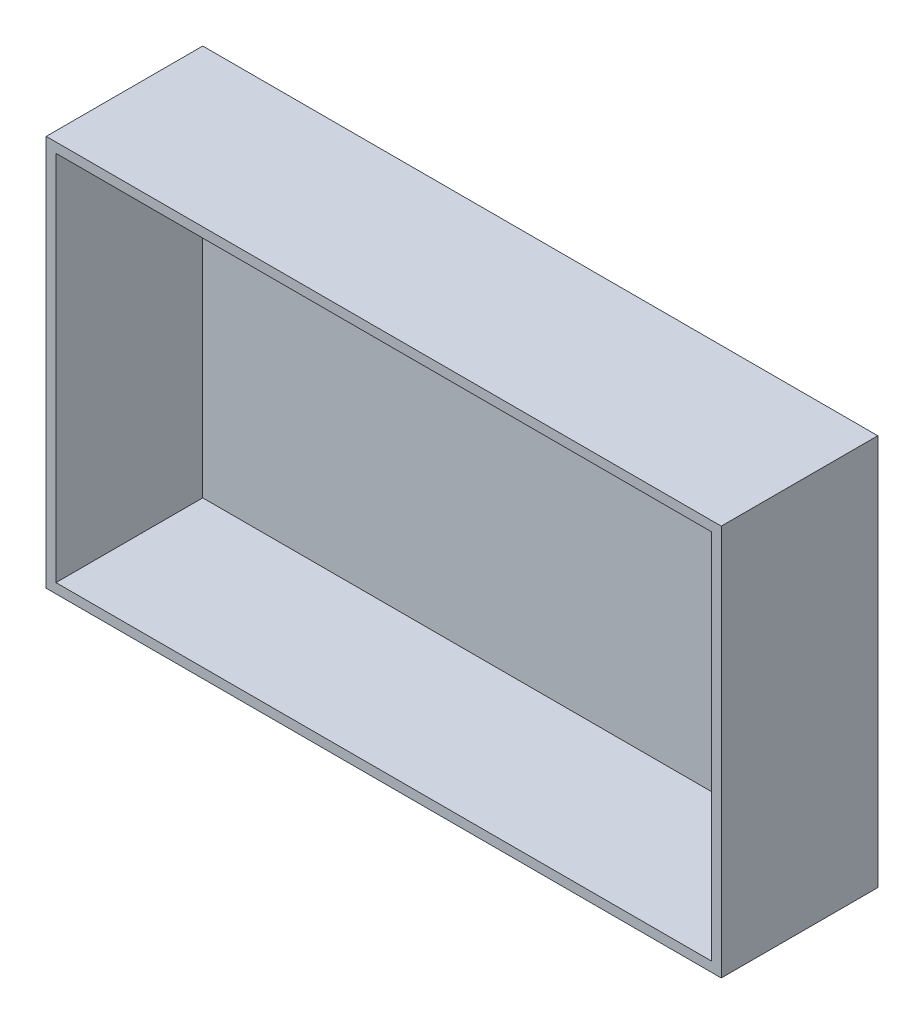
SolidWorks part; units mm, degrees
material "PVC 0.007 plastificato"
ref_plane "Piano frontale" through (0, 0, 0) normal (0, 0, 1) x (1, 0, 0)
ref_plane "Piano superiore" through (0, 0, 0) normal (0, 1, 0) x (1, 0, 0)
ref_plane "Piano destro" through (0, 0, 0) normal (1, 0, 0) x (0, 0, -1)
sketch "Schizzo1" plane through (0, 0, 0) normal (0, 0, 1) x (1, 0, 0)
  line L1 (-345, 200) -> (345, 200)
  line L2 (-345, 200) -> (-345, -200)
  line L3 (-345, -200) -> (345, -200)
  line L4 (345, 200) -> (345, -200)
  line L5 (-345, 200) -> (345, -200) construction
  line L6 (-345, -200) -> (345, 200) construction
  point P0 (0, 0)
  dimension "D1" = 400
  dimension "D2" = 690
extrude "Estrusione-Estrusione1" add sketch "Schizzo1" along normal blind 10
sketch "Schizzo2" plane through (0, 0, 10) normal (0, 0, 1) x (1, 0, 0)
  line L8 (335, -190) -> (335, 190)
  line L9 (335, 190) -> (-335, 190)
  line L10 (-335, 190) -> (-335, -190)
  line L11 (-335, -190) -> (335, -190)
  line L12 (335, -190) -> (335, 190)
  line L13 (335, 190) -> (-335, 190)
  line L14 (-335, 190) -> (-335, -190)
  line L15 (-335, -190) -> (335, -190)
  line L16 (345, -200) -> (345, 200)
  line L17 (345, 200) -> (-345, 200)
  line L18 (-345, 200) -> (-345, -200)
  line L19 (-345, -200) -> (345, -200)
  line L20 (345, -200) -> (345, 200)
  line L21 (345, 200) -> (-345, 200)
  line L22 (-345, 200) -> (-345, -200)
  line L23 (-345, -200) -> (345, -200)
  dimension "D1" = 10
  dimension "D2" = 0
extrude "Estrusione-Estrusione2" add sketch "Schizzo2" along normal blind 150
